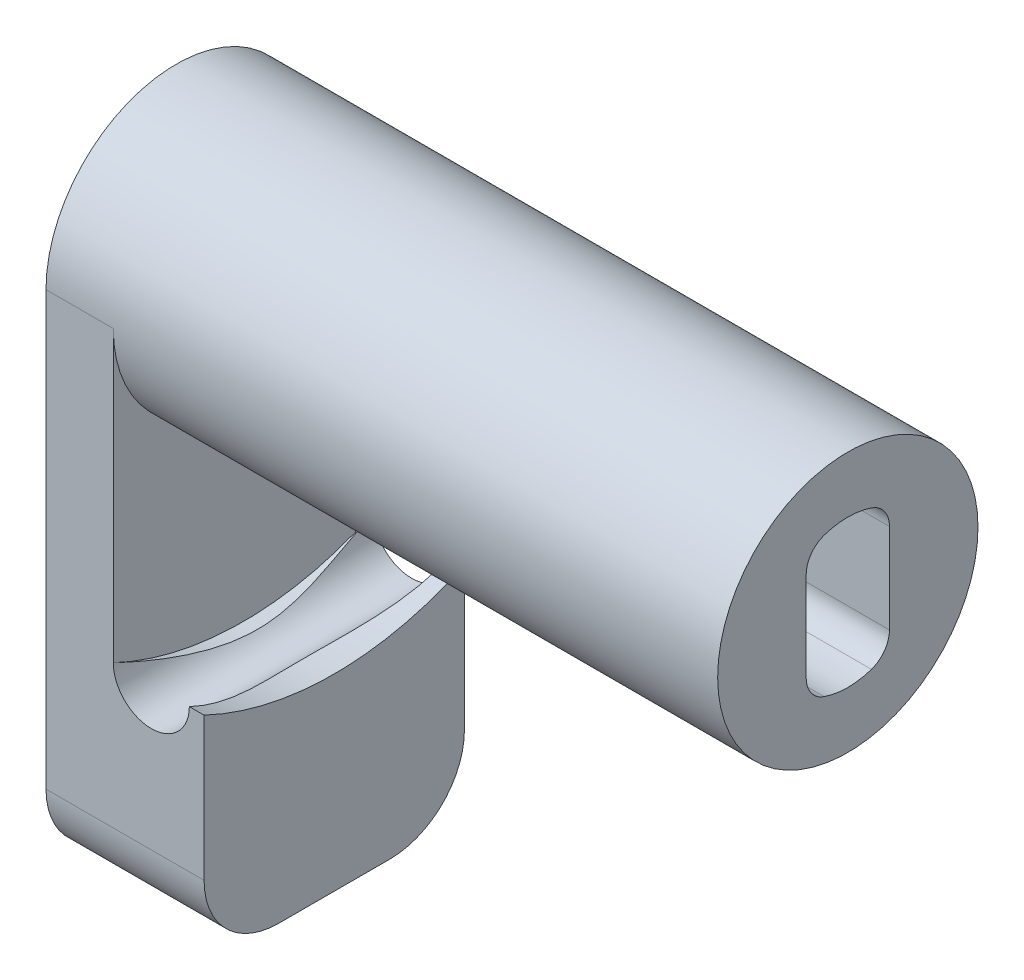
SolidWorks part; units mm, degrees
material "ABS"
ref_plane "Front Plane" through (0, 0, 0) normal (1, 0, 0) x (0, 1, 0)
ref_plane "Top Plane" through (0, 0, 0) normal (0, 0, 1) x (0, 1, 0)
ref_plane "Right Plane" through (0, 0, 0) normal (0, 1, 0) x (-1, 0, 0)
sketch "Sketch1" plane through (0, 0, 0) normal (1, 0, 0) x (0, 1, 0)
  circle A2 centre (0, 0) radius 8.7376
  dimension "D3" = 17.4752
extrude "Boss-Extrude1" add sketch "Sketch1" along normal blind 45.085
sketch "Sketch10" plane through (0, 0, 0) normal (-1, 0, 0) x (0, -1, 0)
  line L0 (0, 8.7376) -> (34.036, 8.7376)
  line L2 (34.036, 8.7376) -> (34.036, -8.7376)
  line L3 (34.036, -8.7376) -> (0, -8.7376)
  circle A0 centre (0, 0) radius 8.7376 construction
  arc A2 (0, 8.7376) -> (0, -8.7376) centre (0, 0) cw
  dimension "D1" = 34.036
extrude "Boss-Extrude3" add sketch "Sketch10" against normal blind 4.516 contours L0 A2 L3 L2
fillet "Fillet2" radius 5 2 edges at (2.258, -34.036, 8.7376) (2.258, -34.036, -8.7376)
sketch "Sketch14" [suppressed] plane through (0, 0, 0) normal (-1, 0, 0) x (0, 0, 1)
  line L0 (0.5115, -3.4237) -> (0.3944, -4.0089)
  line L1 (0, 0) -> (0, -4.064) construction
  line L2 (0, 0) -> (0.5606, -3.4335) construction
  line L3 (0.6039, -3.4087) -> (0.9011, -3.9262)
  line L4 (-0.6903, -3.3922) -> (-1.0005, -3.9021)
  line L5 (-0.5983, -3.4096) -> (-0.4961, -3.9976)
  line L6 (-1.8089, -2.9515) -> (-2.2748, -3.3245)
  line L7 (-1.7284, -2.9994) -> (-1.8334, -3.5869)
  line L8 (-2.7093, -2.1549) -> (-3.2746, -2.346)
  line L9 (-2.65, -2.2273) -> (-2.9496, -2.7435)
  line L10 (-3.2829, -1.0983) -> (-3.8795, -1.0846)
  line L11 (-3.252, -1.1867) -> (-3.7101, -1.5692)
  line L12 (-3.4605, 0.0907) -> (-4.0165, 0.3077)
  line L13 (-3.4617, -0.0029) -> (-4.023, -0.2057)
  line L14 (-3.2208, 1.2689) -> (-3.669, 1.6629)
  line L15 (-3.2539, 1.1813) -> (-3.8507, 1.1827)
  line L16 (-2.5926, 2.2939) -> (-2.879, 2.8175)
  line L17 (-2.6537, 2.223) -> (-3.214, 2.4284)
  line L18 (-1.6517, 3.0423) -> (-1.7417, 3.6323)
  line L19 (-1.7333, 2.9965) -> (-2.1896, 3.3812)
  line L20 (-0.5115, 3.4237) -> (-0.3944, 4.0089)
  line L21 (-0.6039, 3.4087) -> (-0.9011, 3.9262)
  line L22 (0.6903, 3.3922) -> (1.0005, 3.9021)
  line L23 (0.5983, 3.4096) -> (0.4961, 3.9976)
  line L24 (1.8089, 2.9515) -> (2.2748, 3.3245)
  line L25 (1.7284, 2.9994) -> (1.8334, 3.5869)
  line L26 (2.7093, 2.1549) -> (3.2746, 2.346)
  line L27 (2.65, 2.2273) -> (2.9496, 2.7435)
  line L28 (3.2829, 1.0983) -> (3.8795, 1.0846)
  line L29 (3.252, 1.1867) -> (3.7101, 1.5692)
  line L30 (3.4605, -0.0907) -> (4.0165, -0.3077)
  line L31 (3.4617, 0.0029) -> (4.023, 0.2057)
  line L32 (3.2208, -1.2689) -> (3.669, -1.6629)
  line L33 (3.2539, -1.1813) -> (3.8507, -1.1827)
  line L34 (2.5926, -2.2939) -> (2.879, -2.8175)
  line L35 (2.6537, -2.223) -> (3.214, -2.4284)
  line L36 (1.6517, -3.0423) -> (1.7417, -3.6323)
  line L37 (1.7333, -2.9965) -> (2.1896, -3.3812)
  line L38 (-0.1032, -4.0627) -> (0, -4.064)
  line L39 (-1.4865, -3.7824) -> (-1.39, -3.8189)
  line L40 (-2.6905, -3.0459) -> (-2.6123, -3.1132)
  line L41 (-3.5195, -2.032) -> (-3.57, -1.942)
  line L42 (-4.0023, -0.7057) -> (-4.0189, -0.6039)
  line L43 (-4.0023, 0.7057) -> (-3.9831, 0.8071)
  line L44 (-3.5195, 2.032) -> (-3.4668, 2.1207)
  line L45 (-2.6123, 3.1132) -> (-2.5324, 3.1785)
  line L46 (-1.39, 3.8189) -> (-1.2926, 3.853)
  line L47 (0, 4.064) -> (0.1032, 4.0627)
  line L48 (1.39, 3.8189) -> (1.4865, 3.7824)
  line L49 (2.6123, 3.1132) -> (2.6905, 3.0459)
  line L50 (3.5195, 2.032) -> (3.57, 1.942)
  line L51 (4.0023, 0.7057) -> (4.0189, 0.6039)
  line L52 (4.0023, -0.7057) -> (3.9831, -0.8071)
  line L53 (3.5195, -2.032) -> (3.4668, -2.1207)
  line L54 (2.6123, -3.1132) -> (2.5324, -3.1785)
  line L55 (1.39, -3.8189) -> (1.2926, -3.853)
  arc A0 (0.3497, -4.0489) -> (0, -4.064) centre (0, 0) cw
  arc A1 (0.3497, -4.0489) -> (0.3944, -4.0089) centre (0.3454, -3.9991) ccw
  arc A2 (0.5115, -3.4237) -> (0.6039, -3.4087) centre (0.5606, -3.4335) cw
  arc A3 (0.4203, -4.0631) -> (0.3944, -4.0089) centre (0.4434, -4.0187) cw
  arc A4 (0.4203, -4.0631) -> (0.7372, -4.2116) centre (2.3016, -0.4608) ccw
  arc A6 (0.9562, -3.9499) -> (0.9011, -3.9262) centre (0.9445, -3.9013) cw
  arc A7 (0.9562, -3.9499) -> (1.2926, -3.853) centre (0, 0) ccw
  arc A8 (-1.0562, -3.9243) -> (-1.39, -3.8189) centre (0, 0) cw
  arc A9 (-1.0562, -3.9243) -> (-1.0005, -3.9021) centre (-1.0432, -3.8761) ccw
  arc A10 (-0.6903, -3.3922) -> (-0.5983, -3.4096) centre (-0.6476, -3.4182) cw
  arc A11 (-0.4524, -4.0387) -> (-0.4961, -3.9976) centre (-0.4468, -3.9891) cw
  arc A12 (-0.4524, -4.0387) -> (-0.1032, -4.0627) centre (0, 0) ccw
  arc A13 (-2.3347, -3.3264) -> (-2.6123, -3.1132) centre (0, 0) cw
  arc A14 (-2.3347, -3.3264) -> (-2.2748, -3.3245) centre (-2.306, -3.2855) ccw
  arc A15 (-1.8089, -2.9515) -> (-1.7284, -2.9994) centre (-1.7776, -2.9906) cw
  arc A16 (-1.8064, -3.6405) -> (-1.8334, -3.5869) centre (-1.7842, -3.5957) cw
  arc A17 (-1.8064, -3.6405) -> (-1.4865, -3.7824) centre (0, 0) ccw
  arc A18 (-3.3316, -2.3273) -> (-3.5195, -2.032) centre (0, 0) cw
  arc A19 (-3.3316, -2.3273) -> (-3.2746, -2.346) centre (-3.2906, -2.2987) ccw
  arc A20 (-2.7093, -2.1549) -> (-2.65, -2.2273) centre (-2.6933, -2.2022) cw
  arc A21 (-2.9426, -2.8031) -> (-2.9496, -2.7435) centre (-2.9064, -2.7686) cw
  arc A22 (-2.9426, -2.8031) -> (-2.6905, -3.0459) centre (0, 0) ccw
  arc A23 (-3.9267, -1.0475) -> (-4.0023, -0.7057) centre (0, 0) cw
  arc A24 (-3.9267, -1.0475) -> (-3.8795, -1.0846) centre (-3.8784, -1.0346) ccw
  arc A25 (-3.2829, -1.0983) -> (-3.252, -1.1867) centre (-3.284, -1.1483) cw
  arc A26 (-3.7238, -1.6276) -> (-3.7101, -1.5692) centre (-3.678, -1.6076) cw
  arc A27 (-3.7238, -1.6276) -> (-3.57, -1.942) centre (0, 0) ccw
  arc A28 (-4.0481, 0.3587) -> (-4.0023, 0.7057) centre (0, 0) cw
  arc A29 (-4.0481, 0.3587) -> (-4.0165, 0.3077) centre (-3.9983, 0.3543) ccw
  arc A30 (-3.4605, 0.0907) -> (-3.4617, -0.0029) centre (-3.4787, 0.0442) cw
  arc A31 (-4.0559, -0.2558) -> (-4.023, -0.2057) centre (-4.006, -0.2527) cw
  arc A32 (-4.0559, -0.2558) -> (-4.0189, -0.6039) centre (0, 0) ccw
  arc A33 (-3.6813, 1.7216) -> (-3.5195, 2.032) centre (0, 0) cw
  arc A34 (-3.6813, 1.7216) -> (-3.669, 1.6629) centre (-3.636, 1.7005) ccw
  arc A35 (-3.2208, 1.2689) -> (-3.2539, 1.1813) centre (-3.2538, 1.2313) cw
  arc A36 (-3.8988, 1.1468) -> (-3.8507, 1.1827) centre (-3.8509, 1.1327) cw
  arc A37 (-3.8988, 1.1468) -> (-3.9831, 0.8071) centre (0, 0) ccw
  arc A38 (-2.8705, 2.8769) -> (-2.6123, 3.1132) centre (0, 0) cw
  arc A39 (-2.8705, 2.8769) -> (-2.879, 2.8175) centre (-2.8352, 2.8415) ccw
  arc A40 (-2.5926, 2.2939) -> (-2.6537, 2.223) centre (-2.6365, 2.2699) cw
  arc A41 (-3.2715, 2.4111) -> (-3.214, 2.4284) centre (-3.2312, 2.3815) cw
  arc A42 (-3.2715, 2.4111) -> (-3.4668, 2.1207) centre (0, 0) ccw
  arc A43 (-1.7134, 3.6852) -> (-1.39, 3.8189) centre (0, 0) cw
  arc A44 (-1.7134, 3.6852) -> (-1.7417, 3.6323) centre (-1.6923, 3.6398) ccw
  arc A45 (-1.6517, 3.0423) -> (-1.7333, 2.9965) centre (-1.7011, 3.0348) cw
  arc A46 (-2.2495, 3.3846) -> (-2.1896, 3.3812) centre (-2.2218, 3.343) cw
  arc A47 (-2.2495, 3.3846) -> (-2.5324, 3.1785) centre (0, 0) ccw
  arc A48 (-0.3497, 4.0489) -> (0, 4.064) centre (0, 0) cw
  arc A49 (-0.3497, 4.0489) -> (-0.3944, 4.0089) centre (-0.3454, 3.9991) ccw
  arc A50 (-0.5115, 3.4237) -> (-0.6039, 3.4087) centre (-0.5606, 3.4335) cw
  arc A51 (-0.9562, 3.9499) -> (-0.9011, 3.9262) centre (-0.9445, 3.9013) cw
  arc A52 (-0.9562, 3.9499) -> (-1.2926, 3.853) centre (0, 0) ccw
  arc A53 (1.0562, 3.9243) -> (1.39, 3.8189) centre (0, 0) cw
  arc A54 (1.0562, 3.9243) -> (1.0005, 3.9021) centre (1.0432, 3.8761) ccw
  arc A55 (0.6903, 3.3922) -> (0.5983, 3.4096) centre (0.6476, 3.4182) cw
  arc A56 (0.4524, 4.0387) -> (0.4961, 3.9976) centre (0.4468, 3.9891) cw
  arc A57 (0.4524, 4.0387) -> (0.1032, 4.0627) centre (0, 0) ccw
  arc A58 (2.3347, 3.3264) -> (2.6123, 3.1132) centre (0, 0) cw
  arc A59 (2.3347, 3.3264) -> (2.2748, 3.3245) centre (2.306, 3.2855) ccw
  arc A60 (1.8089, 2.9515) -> (1.7284, 2.9994) centre (1.7776, 2.9906) cw
  arc A61 (1.8064, 3.6405) -> (1.8334, 3.5869) centre (1.7842, 3.5957) cw
  arc A62 (1.8064, 3.6405) -> (1.4865, 3.7824) centre (0, 0) ccw
  arc A63 (3.3316, 2.3273) -> (3.5195, 2.032) centre (0, 0) cw
  arc A64 (3.3316, 2.3273) -> (3.2746, 2.346) centre (3.2906, 2.2987) ccw
  arc A65 (2.7093, 2.1549) -> (2.65, 2.2273) centre (2.6933, 2.2022) cw
  arc A66 (2.9426, 2.8031) -> (2.9496, 2.7435) centre (2.9064, 2.7686) cw
  arc A67 (2.9426, 2.8031) -> (2.6905, 3.0459) centre (0, 0) ccw
  arc A68 (3.9267, 1.0475) -> (4.0023, 0.7057) centre (0, 0) cw
  arc A69 (3.9267, 1.0475) -> (3.8795, 1.0846) centre (3.8784, 1.0346) ccw
  arc A70 (3.2829, 1.0983) -> (3.252, 1.1867) centre (3.284, 1.1483) cw
  arc A71 (3.7238, 1.6276) -> (3.7101, 1.5692) centre (3.678, 1.6076) cw
  arc A72 (3.7238, 1.6276) -> (3.57, 1.942) centre (0, 0) ccw
  arc A73 (4.0481, -0.3587) -> (4.0023, -0.7057) centre (0, 0) cw
  arc A74 (4.0481, -0.3587) -> (4.0165, -0.3077) centre (3.9983, -0.3543) ccw
  arc A75 (3.4605, -0.0907) -> (3.4617, 0.0029) centre (3.4787, -0.0442) cw
  arc A76 (4.0559, 0.2558) -> (4.023, 0.2057) centre (4.006, 0.2527) cw
  arc A77 (4.0559, 0.2558) -> (4.0189, 0.6039) centre (0, 0) ccw
  arc A78 (3.6813, -1.7216) -> (3.5195, -2.032) centre (0, 0) cw
  arc A79 (3.6813, -1.7216) -> (3.669, -1.6629) centre (3.636, -1.7005) ccw
  arc A80 (3.2208, -1.2689) -> (3.2539, -1.1813) centre (3.2538, -1.2313) cw
  arc A81 (3.8988, -1.1468) -> (3.8507, -1.1827) centre (3.8509, -1.1327) cw
  arc A82 (3.8988, -1.1468) -> (3.9831, -0.8071) centre (0, 0) ccw
  arc A83 (2.8705, -2.8769) -> (2.6123, -3.1132) centre (0, 0) cw
  arc A84 (2.8705, -2.8769) -> (2.879, -2.8175) centre (2.8352, -2.8415) ccw
  arc A85 (2.5926, -2.2939) -> (2.6537, -2.223) centre (2.6365, -2.2699) cw
  arc A86 (3.2715, -2.4111) -> (3.214, -2.4284) centre (3.2312, -2.3815) cw
  arc A87 (3.2715, -2.4111) -> (3.4668, -2.1207) centre (0, 0) ccw
  arc A88 (1.7134, -3.6852) -> (1.39, -3.8189) centre (0, 0) cw
  arc A89 (1.7134, -3.6852) -> (1.7417, -3.6323) centre (1.6923, -3.6398) ccw
  arc A90 (1.6517, -3.0423) -> (1.7333, -2.9965) centre (1.7011, -3.0348) cw
  arc A91 (2.2495, -3.3846) -> (2.1896, -3.3812) centre (2.2218, -3.343) cw
  arc A92 (2.2495, -3.3846) -> (2.5324, -3.1785) centre (0, 0) ccw
  point P207 (0, 0)
  dimension "D1" = 4.064
  dimension "D2" = 0.05
  dimension "D3" = 0.05
  dimension "D4" = 0.04
  dimension "D5" = 18
  dimension "D6" = 0.5968
  dimension "D8" = 0.35
sketch "Sketch15" plane through (4.516, 0, 0) normal (1, 0, 0) x (0, 1, 0)
  line L1 (-29.036, 8.7376) -> (-18.796, 8.7376)
  line L2 (-18.796, 8.7376) -> (-18.796, -8.7376)
  line L3 (0, 8.7376) -> (-29.036, 8.7376) construction
  line L4 (-29.036, -8.7376) -> (-18.796, -8.7376)
  line L5 (-34.036, 3.7376) -> (-34.036, -3.7376) construction
  line L6 (-34.036, 3.7376) -> (-34.036, -3.7376)
  line L8 (-29.036, -8.7376) -> (0, -8.7376) construction
  line L13 (0, 8.7376) -> (-29.036, 8.7376)
  line L14 (-34.036, 3.7376) -> (-34.036, -3.7376)
  line L15 (-29.036, -8.7376) -> (0, -8.7376)
  line L17 (-34.036, 3.7376) -> (-34.036, -3.7376)
  arc A0 (-29.036, 8.7376) -> (-34.036, 3.7376) centre (-29.036, 3.7376) ccw construction
  arc A1 (-34.036, -3.7376) -> (-29.036, -8.7376) centre (-29.036, -3.7376) ccw construction
  arc A2 (-29.036, 8.7376) -> (-34.036, 3.7376) centre (-29.036, 3.7376) ccw
  arc A3 (-34.036, -3.7376) -> (-29.036, -8.7376) centre (-29.036, -3.7376) ccw
  arc A7 (-29.036, 8.7376) -> (-34.036, 3.7376) centre (-29.036, 3.7376) ccw
  arc A8 (-34.036, -3.7376) -> (-29.036, -8.7376) centre (-29.036, -3.7376) ccw
  arc A9 (0, 8.7376) -> (0, -8.7376) centre (0, 0) ccw
  arc A10 (-29.036, 8.7376) -> (-34.036, 3.7376) centre (-29.036, 3.7376) ccw
  arc A11 (-34.036, -3.7376) -> (-29.036, -8.7376) centre (-29.036, -3.7376) ccw
  arc A12 (0, 8.7376) -> (0, -8.7376) centre (0, 0) ccw
  point P0 (-18.796, -8.7376)
  dimension "D1" = 15.24
  dimension "D2" = 0
extrude "Boss-Extrude4" add sketch "Sketch15" along normal blind 6.096
sketch "Sketch21" plane through (10.612, 0, 0) normal (1, 0, 0) x (0, 1, 0)
  line L2 (-18.796, -8.7376) -> (-18.796, 8.7376)
  line L4 (-29.036, 8.7376) -> (-18.796, 8.7376) construction
  line L5 (-19.431, -8.7376) -> (-18.796, -8.7376)
  line L6 (-18.796, 8.7376) -> (-18.796, -8.7376) construction
  line L8 (-18.796, -8.7376) -> (0, -8.7376) construction
  line L14 (-18.796, -8.7376) -> (-18.796, 8.7376) construction
  line L20 (-18.796, 8.7376) -> (-29.036, 8.7376)
  arc A2 (-19.431, -8.7376) -> (-19.431, 8.7376) centre (-1.0855, 0) cw
  dimension "D4" = 20.32
  dimension "D2" = 0.635
  dimension "D3" = 0.635
extrude "Cut-Extrude8" cut sketch "Sketch21" against normal up to surface (6.096 mm away)
sketch "Sketch22" plane through (45.085, 0, 0) normal (1, 0, 0) x (0, 1, 0)
  line L7 (-4.0897, -2.794) -> (4.0897, 2.794) construction
  line L8 (-4.0897, 2.794) -> (4.0897, -2.794) construction
  line L11 (-4.0897, -2.794) -> (4.0897, -2.794)
  line L13 (-4.0897, 2.794) -> (4.0897, 2.794)
  line L15 (-4.0897, -2.794) -> (4.0897, 2.794) construction
  line L16 (-4.0897, 2.794) -> (4.0897, -2.794) construction
  arc A3 (-4.0897, 2.794) -> (-4.0897, -2.794) centre (0, 0) ccw
  arc A4 (4.0897, -2.794) -> (4.0897, 2.794) centre (0, 0) ccw
  dimension "D2" = 9.906
  dimension "D3" = 5.588
extrude "Cut-Extrude10" cut sketch "Sketch22" against normal blind 12.192
fillet "Fillet11" radius 1.778 4 edges at (38.989, 4.0897, -2.794) (38.989, 4.0897, 2.794) (38.989, -4.0897, -2.794) (38.989, -4.0897, 2.794)
sketch "Sketch25" plane through (0, 0, -8.7376) normal (0, 0, -1) x (1, 0, 0)
  line L3 (4.516, 19.431) -> (4.516, 0) construction
  line L4 (4.516, 19.431) -> (10.612, 19.431) construction
  circle A0 centre (7.0687, 19.431) radius 2.5527
  dimension "D1" = 5.1054
extrude "Cut-Extrude14" cut sketch "Sketch25" against normal through all
sketch "Sketch26" plane through (0, 0, 0) normal (-1, 0, 0) x (0, -1, 0)
  line L1 (3.7411, 1.5875) -> (5.3921, 1.5875)
  line L2 (3.7411, 1.5875) -> (3.7411, -1.5875) construction
  line L3 (3.7411, -1.5875) -> (5.3921, -1.5875)
  line L4 (5.3921, 1.5875) -> (5.3921, -1.5875)
  arc A0 (3.7411, 1.5875) -> (3.7411, -1.5875) centre (0, 0) ccw
  dimension "D1" = 8.128
  dimension "D2" = 3.175
  dimension "D3" = 1.651
extrude "Cut-Extrude15" cut sketch "Sketch26" against normal blind 21.59
fillet "Fillet12" radius 0.3969 4 edges at (10.795, -3.7411, 1.5875) (10.795, -5.3921, 1.5875) (10.795, -3.7411, -1.5875) (10.795, -5.3921, -1.5875)
